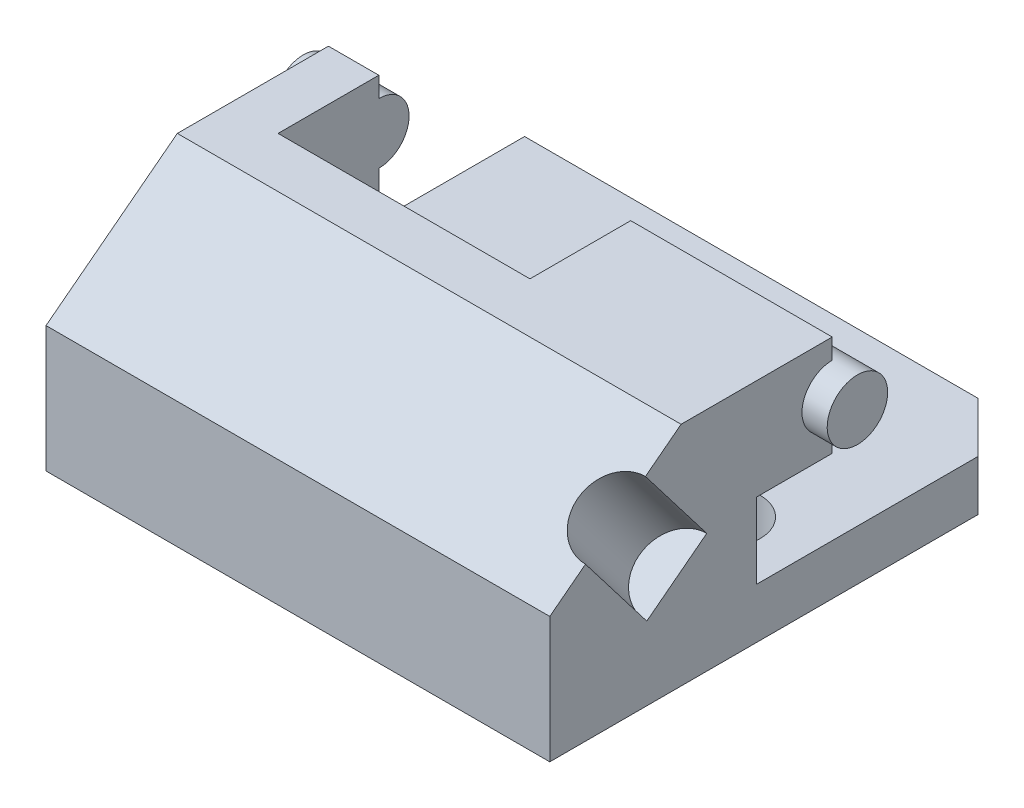
SolidWorks part; units mm, degrees
material "Alliage 1060"
ref_plane "Plan de face" through (0, 0, 0) normal (0, 0, 1) x (1, 0, 0)
ref_plane "Plan de dessus" through (0, 0, 0) normal (0, 1, 0) x (1, 0, 0)
ref_plane "Plan de droite" through (0, 0, 0) normal (1, 0, 0) x (0, 0, -1)
sketch "Esquisse1" plane through (0, 0, 0) normal (1, 0, 0) x (0, 0, -1)
  line L0 (0, 0) -> (53.9355, 0)
  line L1 (53.9355, 0) -> (53.9355, -10)
  line L2 (53.9355, -10) -> (-41.0645, -10)
  line L3 (-41.0645, -10) -> (-41.0645, 15)
  line L4 (-41.0645, 15) -> (-15, 35)
  line L5 (-15, 35) -> (15, 35)
  line L6 (0, 0) -> (0, 15)
  line L7 (0, 15) -> (15, 15)
  line L8 (15, 15) -> (15, 19)
  line L9 (15, 35) -> (15, 31) construction
  line L10 (21, 25) -> (34.0027, 25) construction
  line L11 (15, 31) -> (15, 35)
  circle A0 centre (15, 25) radius 6
  point P7 (53.9355, -5)
  dimension "D1" = 95
  dimension "D2" = 10
  dimension "D3" = 15
  dimension "D4" = 20
  dimension "D6" = 30
  dimension "D5" = 20
  dimension "D7" = 52.5
  dimension "D8" = 15
extrude "Boss.-Extru.1" add sketch "Esquisse1" along normal blind 100 contours A0 L11 L5 L4 L3 L2 L1 L0 L6 L7 L8 | A0
sketch "Esquisse2" plane through (100, 0, 0) normal (1, 0, 0) x (0, 0, -1)
  circle A0 centre (15, 25) radius 6
extrude "Boss.-Extru.2" add sketch "Esquisse2" along normal blind 5
sketch "Esquisse3" plane through (0, 0, 0) normal (-1, 0, 0) x (0, 0, 1)
  circle A0 centre (-15, 25) radius 6
extrude "Boss.-Extru.3" add sketch "Esquisse3" along normal blind 5
sketch "Esquisse4" plane through (0, 29.2738, 22.4626) normal (0, 0.7934, 0.6088) x (1, 0, 0)
  line L0 (100, -23.4472) -> (100, 9.4063) construction
  line L1 (100, 9.4063) -> (100, -7.0204)
  circle A0 centre (100, -7.0204) radius 7.5
  line M3 (100, -23.4472) -> (100, 9.4063)
extrude "Enlèv. mat.-Extru.1" cut sketch "Esquisse4" against normal blind 20 contours A0 M3
sketch "Esquisse5" plane through (0, 35, 0) normal (0, 1, 0) x (1, 0, 0)
  line L0 (0, 15) -> (10, 15)
  line L1 (10, 15) -> (10, -5)
  line L2 (10, -5) -> (60, -5)
  line L3 (60, -5) -> (60, 21)
  line L4 (105, 21) -> (-5, 21) construction
  line L6 (10, 21) -> (10, 15)
  line L7 (0, -15) -> (0, 15) construction
  line L8 (10, 21) -> (10, 25.1377)
  line L9 (10, 25.1377) -> (60, 25.1377)
  line L10 (60, 25.1377) -> (60, 21)
  line L11 (100, -15) -> (0, -15) construction
  line M9 (100, 15) -> (0, 15)
  dimension "D1" = 50
  dimension "D2" = 10
  dimension "D3" = 10
extrude "Enlèv. mat.-Extru.3" cut sketch "Esquisse5" against normal up to surface (35 mm away) contours L2 L3 L1 M9 up to face at (50, 0, -26.9677)
sketch "Esquisse6" plane through (0, 0, 0) normal (0, 1, 0) x (1, 0, 0)
  line L0 (10, 15) -> (10, 21)
  line L1 (105, 21) -> (-5, 21) construction
  line L2 (60, 15) -> (60, 21)
  line L3 (60, 21) -> (10, 21)
  line L4 (10, 15) -> (60, 15)
extrude "Enlèv. mat.-Extru.4" cut sketch "Esquisse6" along normal blind 40
sketch "Esquisse7" plane through (0, -10, 0) normal (0, -1, 0) x (1, 0, 0)
  line L0 (0, -53.9355) -> (0, -8.149)
  line L1 (0, -53.9355) -> (0, 41.0645) construction
  line L2 (0, -8.149) -> (15, -8.149)
  line L3 (15, -8.149) -> (35, -8.149)
  line L4 (35, -8.149) -> (65, -8.149)
  line L5 (65, -8.149) -> (85, -8.149)
  line L6 (85, -8.149) -> (100, -8.149)
  line L7 (100, -53.9355) -> (100, 41.0645) construction
  line L8 (35, -8.149) -> (65, -8.149) construction
  line L9 (35, -0.649) -> (65, -0.649)
  line L10 (35, -15.649) -> (65, -15.649)
  circle A0 centre (15, -8.149) radius 7.5
  circle A1 centre (85, -8.149) radius 7.5
  arc A2 (35, -0.649) -> (35, -15.649) centre (35, -8.149) ccw
  arc A3 (65, -15.649) -> (65, -0.649) centre (65, -8.149) ccw
  point P14 (50, -8.149)
extrude "Enlèv. mat.-Extru.5" cut sketch "Esquisse7" against normal blind 10 contours L3 A0 L2 | L2 A0 L3 | L5 A3 L9 A2 L3 L4 | L10 A3 L5 L4 L3 A2 | L6 A1 L5 | L5 A1 L6
sketch "Esquisse8" plane through (0, -10, 0) normal (0, -1, 0) x (1, 0, 0)
  line L0 (100, -53.9355) -> (100, -43.9355)
  line L1 (100, -53.9355) -> (100, 41.0645) construction
  line L2 (100, -43.9355) -> (90, -53.9355)
  line L3 (100, -53.9355) -> (0, -53.9355) construction
  line L4 (90, -53.9355) -> (100, -53.9355)
  dimension "D1" = 10
  dimension "D2" = 45
extrude "Enlèv. mat.-Extru.6" cut sketch "Esquisse8" against normal blind 10
equation "\"A\"= 95"
equation "\"B\"= 50"
equation "\"C\"= 52.5"
equation "\"D1@Esquisse1\"=\"A\""
equation "\"D7@Esquisse1\"=\"C\""
equation "\"D1@Esquisse5\"=\"B\""
